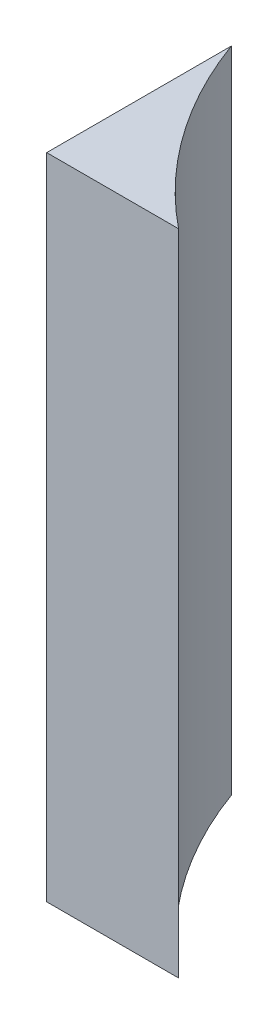
SolidWorks part; units mm, degrees
ref_plane "Front" through (0, 0, 0) normal (0, 0, 1) x (1, 0, 0)
ref_plane "Top" through (0, 0, 0) normal (0, 1, 0) x (1, 0, 0)
ref_plane "Right" through (0, 0, 0) normal (1, 0, 0) x (0, 0, -1)
sketch "Sketch1" plane through (0, 0, 0) normal (0, 1, 0) x (1, 0, 0)
  line L0 (0, 0) -> (0, 35)
  line L2 (25, 0) -> (0, 0)
  arc A0 (0, 35) -> (25, 0) centre (75.2024, 62.2874) ccw
  dimension "D1" = 35
  dimension "D2" = 25
extrude "Boss-Extrude1" add sketch "Sketch1" along normal blind 123
